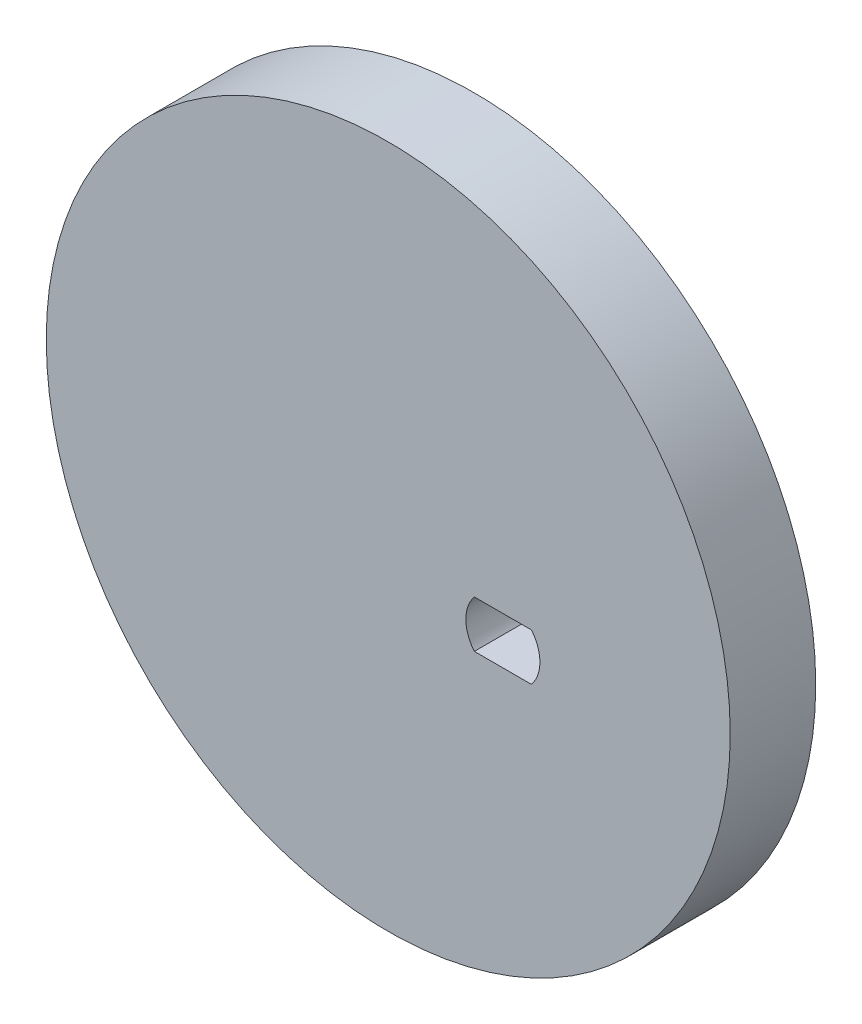
SolidWorks part; units mm, degrees
ref_plane "Front Plane" through (0, 0, 0) normal (0, 0, 1) x (1, 0, 0)
ref_plane "Top Plane" through (0, 0, 0) normal (0, 1, 0) x (1, 0, 0)
ref_plane "Right Plane" through (0, 0, 0) normal (1, 0, 0) x (0, 0, -1)
sketch "Sketch1" plane through (0, 0, 0) normal (0, 0, 1) x (1, 0, 0)
  line L4 (-2.1213, 1.75) -> (2.1213, 1.75)
  line L5 (-2.1213, -1.75) -> (2.1213, -1.75)
  arc A10 (-2.1213, 1.75) -> (-2.1213, -1.75) centre (0, 0) ccw
  arc A11 (2.1213, 1.75) -> (2.1213, -1.75) centre (0, 0) cw
  circle A15 centre (-8.5147, 2.4305) radius 25.4
  dimension "D1" = 4.2426
  dimension "D2" = 4.2426
  dimension "D3" = 2.75
  dimension "D4" = 2.75
  dimension "2" = 50.8
extrude "Boss-Extrude1" add sketch "Sketch1" along normal blind 6.35
